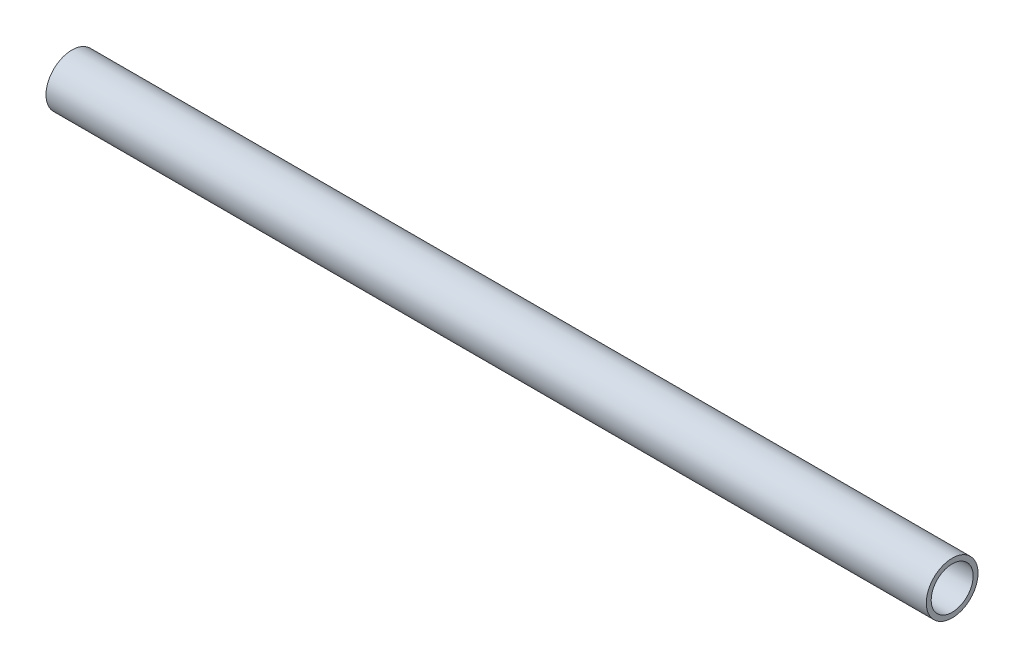
SolidWorks part; units mm, degrees
material "AISI 4130 Steel, annealed at 865C"
ref_plane "X-Y Datum" through (0, 0, 0) normal (0, 0, 1) x (1, 0, 0)
ref_plane "X-Z Datum" through (0, 0, 0) normal (0, 1, 0) x (1, 0, 0)
ref_plane "Y-Z Datum" through (0, 0, 0) normal (1, 0, 0) x (0, 0, -1)
sketch3d "3DSketch1"
  line L0 (348.9566, 0, -5.6165) -> (-82.8434, 0, -5.6165)
  dimension "D1" = 431.8
other "Al round tubing AL RND TUBE 1 OD X 0.095 WALL(1)"
ref_plane "Plane1" through (348.9566, 0, -5.6165) normal (-1, 0, 0) x (0, 0, 1)
sketch "Sketch113" plane through (348.9566, 0, -5.6165) normal (-1, 0, 0) x (0, 0, 1)
  circle A0 centre (0, 0) radius 10.287
  circle A1 centre (0, 0) radius 12.7
  point P3 (0, 0)
  dimension "In_dia" = 20.574
  dimension "Out_dia" = 25.4
